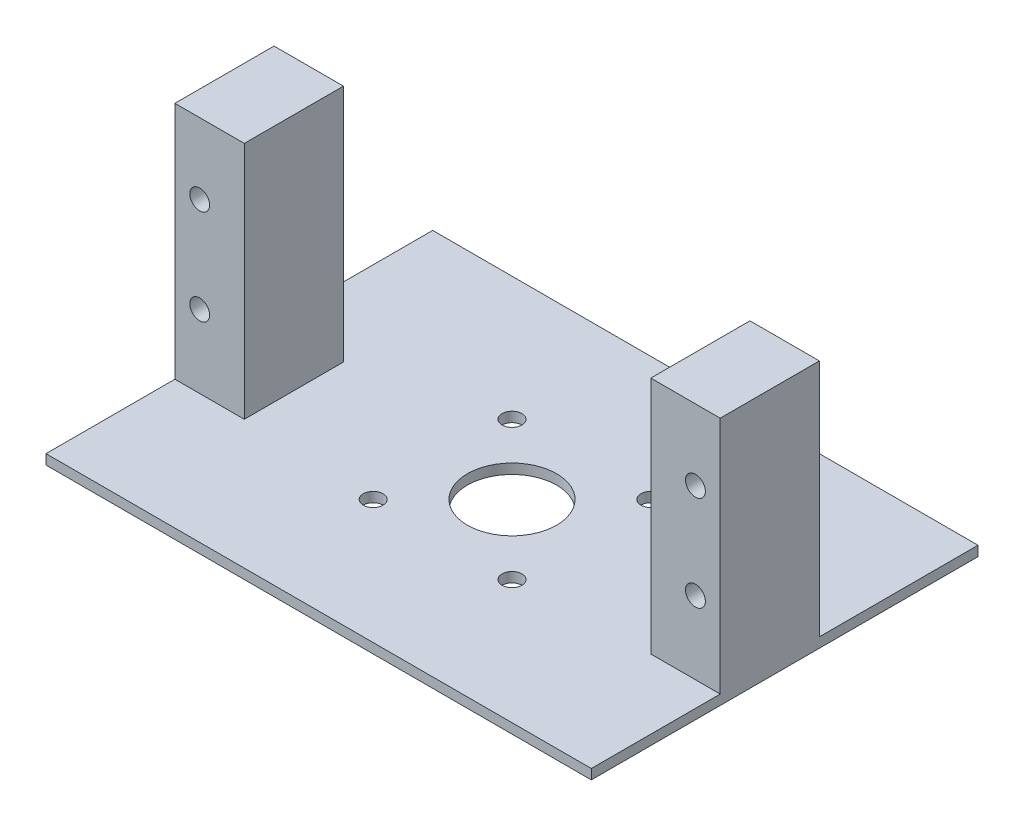
SolidWorks part; units mm, degrees
ref_plane "Front Plane" through (0, 0, 0) normal (0, 0, 1) x (1, 0, 0)
ref_plane "Top Plane" through (0, 0, 0) normal (0, 1, 0) x (1, 0, 0)
ref_plane "Right Plane" through (0, 0, 0) normal (1, 0, 0) x (0, 0, -1)
sketch "Sketch1" plane through (0, 0, 0) normal (0, 1, 0) x (1, 0, 0)
  line L1 (0, 0) -> (55, 0)
  line L2 (0, 0) -> (0, 39)
  line L3 (0, 39) -> (55, 39)
  line L4 (55, 0) -> (55, 39)
  dimension "D1" = 55
  dimension "D2" = 39
extrude "Boss-Extrude1" add sketch "Sketch1" along normal blind 1
sketch "Sketch2" plane through (0, 1, 0) normal (0, 1, 0) x (1, 0, 0)
  line L0 (27.5, 39) -> (27.5, 0) construction
  line L1 (55, 39) -> (0, 39) construction
  line L2 (0, 0) -> (55, 0) construction
  line L3 (48, 39) -> (48, 0) construction
  line L4 (0, 19.5) -> (55, 19.5) construction
  line L5 (0, 39) -> (0, 0) construction
  line L6 (55, 0) -> (55, 39) construction
  line L7 (55, 13) -> (55, 23)
  line L8 (55, 23) -> (48, 23)
  line L9 (48, 23) -> (48, 13)
  line L10 (48, 13) -> (55, 13)
  line L11 (7, 23) -> (7, 13)
  line L12 (0, 23) -> (7, 23)
  line L13 (0, 13) -> (0, 23)
  line L14 (7, 13) -> (0, 13)
  point P6 (48, 39)
  point P16 (55, 13)
  dimension "D1" = 7
  dimension "D2" = 26
  dimension "D3" = 10
sketch "Sketch3" plane through (0, 1, 0) normal (0, 1, 0) x (1, 0, 0)
  line L0 (27.5, 39) -> (27.5, 0) construction
  line L1 (0, 19.5) -> (55, 19.5) construction
  circle A0 centre (34.5, 26.5) radius 1
  circle A1 centre (34.5, 12.5) radius 1
  circle A2 centre (20.5, 12.5) radius 1
  circle A3 centre (20.5, 26.5) radius 1
  circle A4 centre (27.5, 19.5) radius 4.5
  point P10 (27.5, 19.5)
  dimension "D1" = 8
  dimension "D2" = 8
  dimension "D4" = 9
  dimension "D5" = 2
  dimension "D3" = 4
extrude "Cut-Extrude1" cut sketch "Sketch3" against normal up to next
extrude "Boss-Extrude2" add sketch "Sketch2" along normal blind 24.1
sketch "Sketch4" plane through (0, 0, -13) normal (0, 0, 1) x (1, 0, 0)
  line L0 (27.5, 1) -> (27.5, 32.1935) construction
  line L1 (0, 25.1) -> (0, 1.2) construction
  line L2 (0, 25.1) -> (0, 1) construction
  line L3 (0, 1.2) -> (7, 25.1) construction
  line L4 (2.4488, 13.15) -> (-6.0255, 13.15) construction
  circle A0 centre (2.5, 17.95) radius 1
  circle A1 centre (2.5, 8.35) radius 1
  circle A2 centre (52.5, 8.35) radius 1
  circle A3 centre (52.5, 17.95) radius 1
  dimension "D3" = 2.5
  dimension "D4" = 2
  dimension "D1" = 23.9
  dimension "D2" = 4.8
extrude "Cut-Extrude2" cut sketch "Sketch4" against normal up to next
